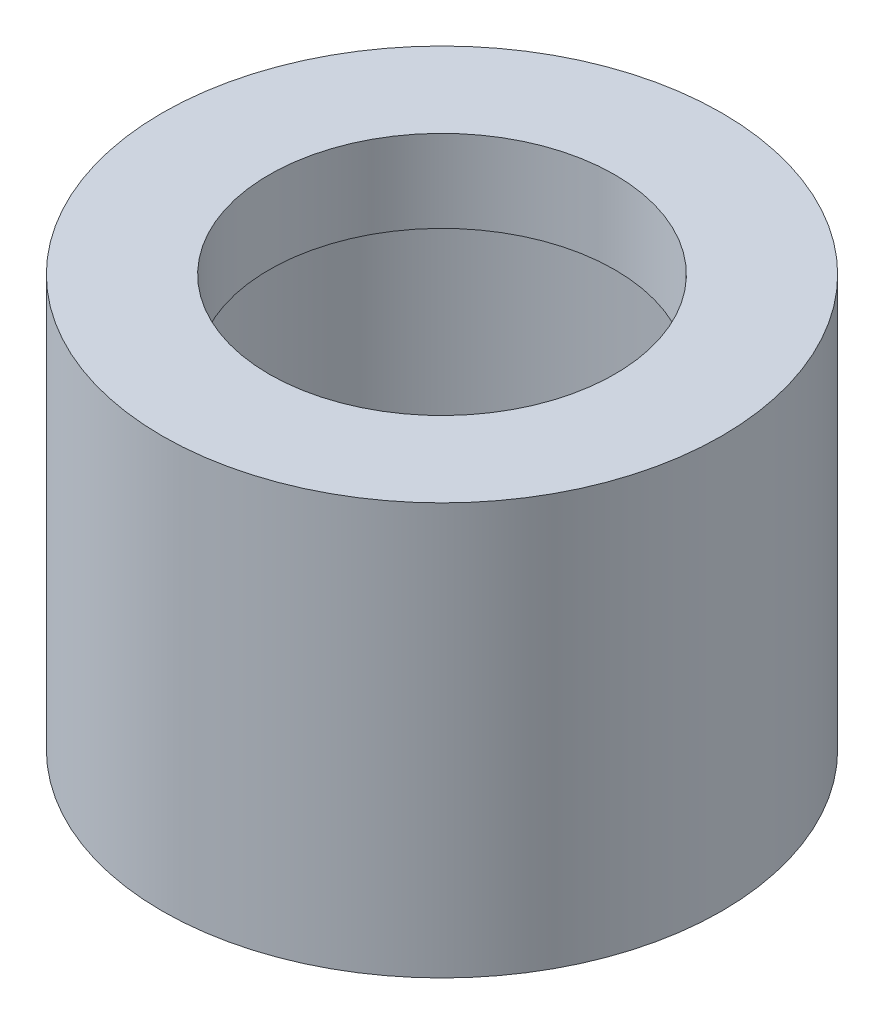
SolidWorks part; units mm, degrees
material "ABS"
ref_plane "Front Plane" through (0, 0, 0) normal (0, 0, 1) x (1, 0, 0)
ref_plane "Top Plane" through (0, 0, 0) normal (0, 1, 0) x (1, 0, 0)
ref_plane "Right Plane" through (0, 0, 0) normal (1, 0, 0) x (0, 0, -1)
sketch "Sketch1" plane through (0, 0, 0) normal (0, 1, 0) x (1, 0, 0)
  circle A0 centre (0, 0) radius 15
  circle A1 centre (0, 0) radius 17
  dimension "D1" = 30
  dimension "D2" = 2
extrude "Boss-Extrude1" add sketch "Sketch1" along normal blind 20
sketch "Sketch2" plane through (0, 20, 0) normal (0, 1, 0) x (1, 0, 0)
  circle A0 centre (0, 0) radius 17
  circle A1 centre (0, 0) radius 17 construction
  circle A2 centre (0, 0) radius 5
  circle A3 centre (0, 0) radius 10.5
  circle M4 centre (0, 0) radius 17
  circle M5 centre (0, 0) radius 15
  dimension "D1" = 10
  dimension "D2" = 21
extrude "Boss-Extrude2" add sketch "Sketch2" along normal blind 5 contours A3 M5 | M4 M5
